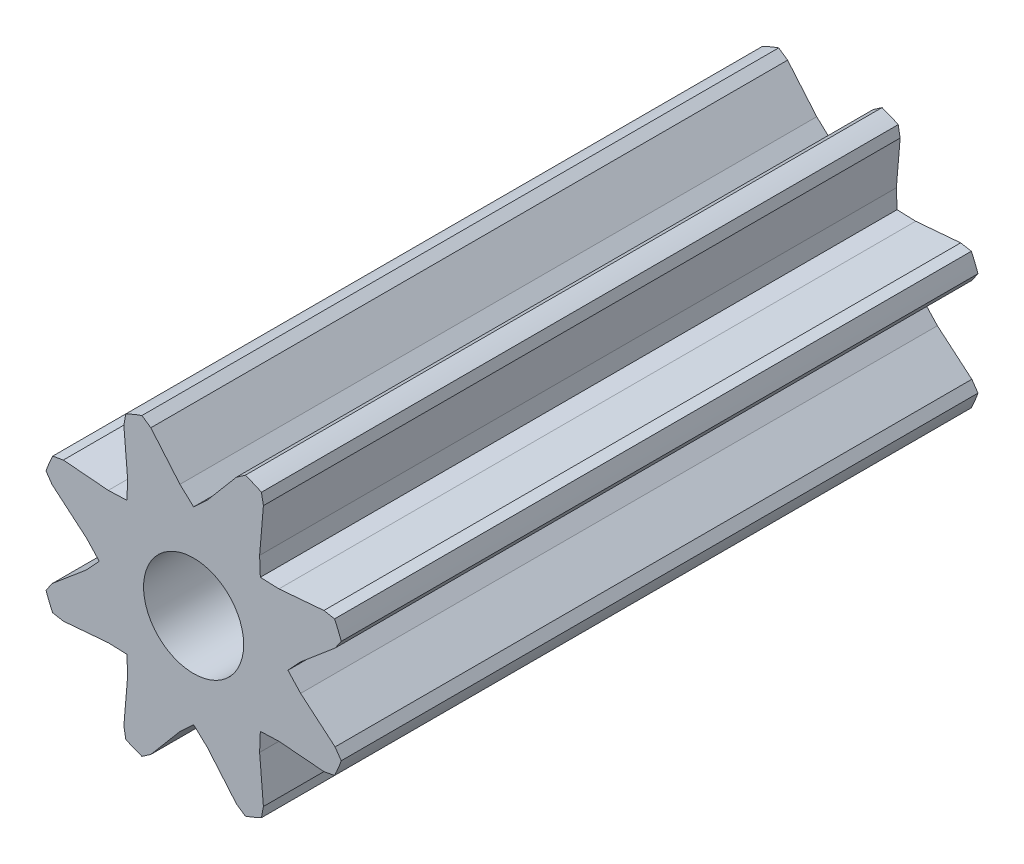
SolidWorks part; units mm, degrees
ref_plane "Front Plane" through (0, 0, 0) normal (0, 0, 1) x (1, 0, 0)
ref_plane "Top Plane" through (0, 0, 0) normal (0, 1, 0) x (1, 0, 0)
ref_plane "Right Plane" through (0, 0, 0) normal (1, 0, 0) x (0, 0, -1)
sketch "Sketch1" plane through (0, 0, 0) normal (0, 0, 1) x (1, 0, 0)
  line L1 (1.2374, -1.2374) -> (-1.2374, -1.2374) construction
  line L2 (1.2374, -1.2374) -> (1.2374, 1.2374) construction
  line L3 (1.2374, 1.2374) -> (-1.2374, 1.2374) construction
  line L4 (-1.2374, -1.2374) -> (-1.2374, 1.2374) construction
  line L5 (1.2374, -1.2374) -> (-1.2374, 1.2374) construction
  line L6 (1.2374, 1.2374) -> (-1.2374, -1.2374) construction
  circle A0 centre (0, 0) radius 5
  circle A1 centre (0, 0) radius 1.75 construction
  dimension "D1" = 10
  dimension "D2" = 3.5
extrude "Boss-Extrude1" add sketch "Sketch1" along normal blind 20.355
sketch "Sketch2" plane through (0, 0, 0) normal (0, 0, 1) x (1, 0, 0)
  line L0 (0, 0) -> (0, 8.8612) construction
  line L1 (0, 3.0153) -> (-0.4371, 3.4206)
  line L8 (-1.8991, 5.2712) -> (0, 6.2652)
  line L11 (-0.4371, 3.4206) -> (-1.3679, 4.5219)
  line L12 (-1.3679, 4.5219) -> (-1.6525, 4.719)
  line L13 (-1.6525, 4.719) -> (-1.8991, 5.2712)
  line L14 (1.6525, 4.719) -> (1.8991, 5.2712)
  line L15 (1.3679, 4.5219) -> (1.6525, 4.719)
  line L16 (0.4371, 3.4206) -> (1.3679, 4.5219)
  line L17 (1.8991, 5.2712) -> (0, 6.2652)
  line L18 (0, 3.0153) -> (0.4371, 3.4206)
  circle A14 centre (0, 0) radius 5 construction
  point P16 (0, 5)
extrude "Cut-Extrude1" cut sketch "Sketch2" along normal through all
pattern_circular "CirPattern1" count 8 over 360 about axis through (0, 0, 0) along (0, 0, 1) of "Cut-Extrude1"
sketch "Sketch3" plane through (0, 0, 0) normal (0, 0, 1) x (1, 0, 0)
  circle A0 centre (0, 0) radius 7.5
  dimension "D1" = 15
sketch "Sketch4" plane through (0, 0, 20.355) normal (0, 0, 1) x (1, 0, 0)
  circle A0 centre (0, 0) radius 1.6
  dimension "D1" = 3.2
extrude "Cut-Extrude2" cut sketch "Sketch4" against normal through all both and the other way through all
sketch "Sketch5" plane through (0, 0, 0) normal (0, 0, 1) x (1, 0, 0)
  line L0 (-1.2374, 1.2374) -> (1.2374, -1.2374)
  line L1 (1.2374, 1.2374) -> (-1.2374, -1.2374)
equation "\"circle\"=10"
equation "\"D1@Sketch1\"=\"circle\""
